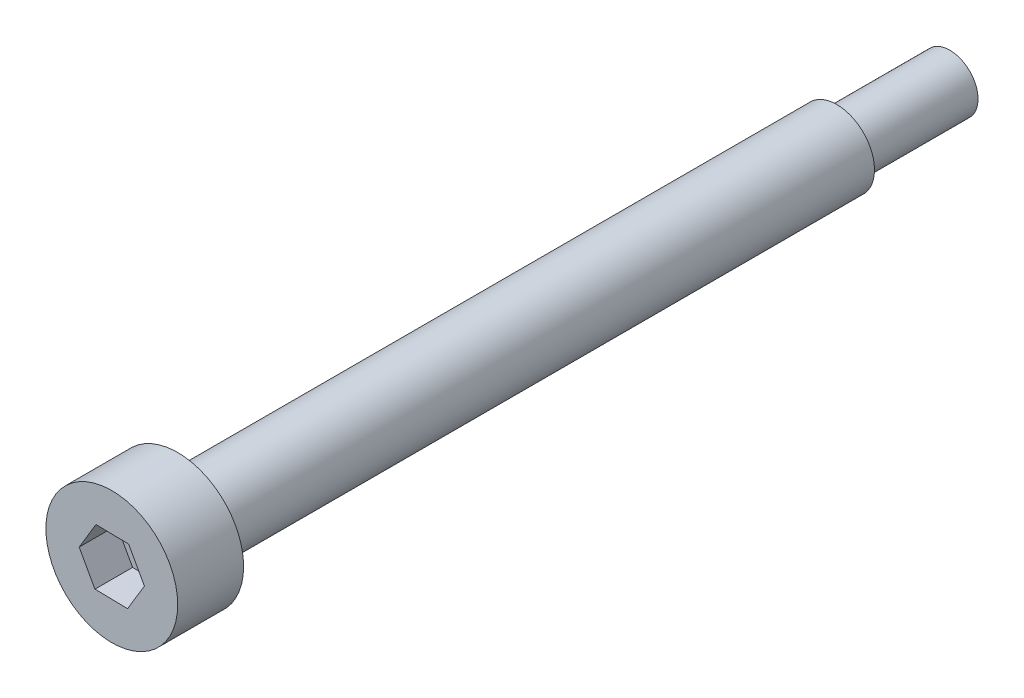
SolidWorks part; units mm, degrees
material "AISI 304"
ref_plane "前视基准面" through (0, 0, 0) normal (0, 0, 1) x (1, 0, 0)
ref_plane "上视基准面" through (0, 0, 0) normal (0, 1, 0) x (1, 0, 0)
ref_plane "右视基准面" through (0, 0, 0) normal (1, 0, 0) x (0, 0, -1)
sketch "草图1" plane through (0, 0, 0) normal (0, 0, 1) x (1, 0, 0)
  circle A0 centre (0, 0) radius 3.5
  dimension "D1" = 7
extrude "凸台-拉伸1" add sketch "草图1" along normal blind 3.5
sketch "草图2" plane through (0, 0, 3.5) normal (0, 0, 1) x (1, 0, 0)
  line L1 (0.8936, 1.4837) -> (-0.8381, 1.5158)
  line L2 (-0.8381, 1.5158) -> (-1.7318, 0.0321)
  line L3 (-1.7318, 0.0321) -> (-0.8936, -1.4837)
  line L4 (-0.8936, -1.4837) -> (0.8381, -1.5158)
  line L5 (0.8381, -1.5158) -> (1.7318, -0.0321)
  line L6 (1.7318, -0.0321) -> (0.8936, 1.4837)
  circle A0 centre (0, 0) radius 1.5 construction
  dimension "D1" = 3
extrude "切除-拉伸1" cut sketch "草图2" against normal blind 2
sketch "草图3" plane through (0, 0, 0) normal (0, 0, -1) x (-1, 0, 0)
  circle A0 centre (0, 0) radius 2
  dimension "D1" = 4
extrude "凸台-拉伸2" add sketch "草图3" along normal blind 35
sketch "草图4" plane through (0, 0, -35) normal (0, 0, -1) x (-1, 0, 0)
  circle A0 centre (0, 0) radius 1.5
  dimension "D1" = 3
extrude "凸台-拉伸3" add sketch "草图4" along normal blind 6
cosmetic thread "装饰螺纹线1" parameters "D2"=2
